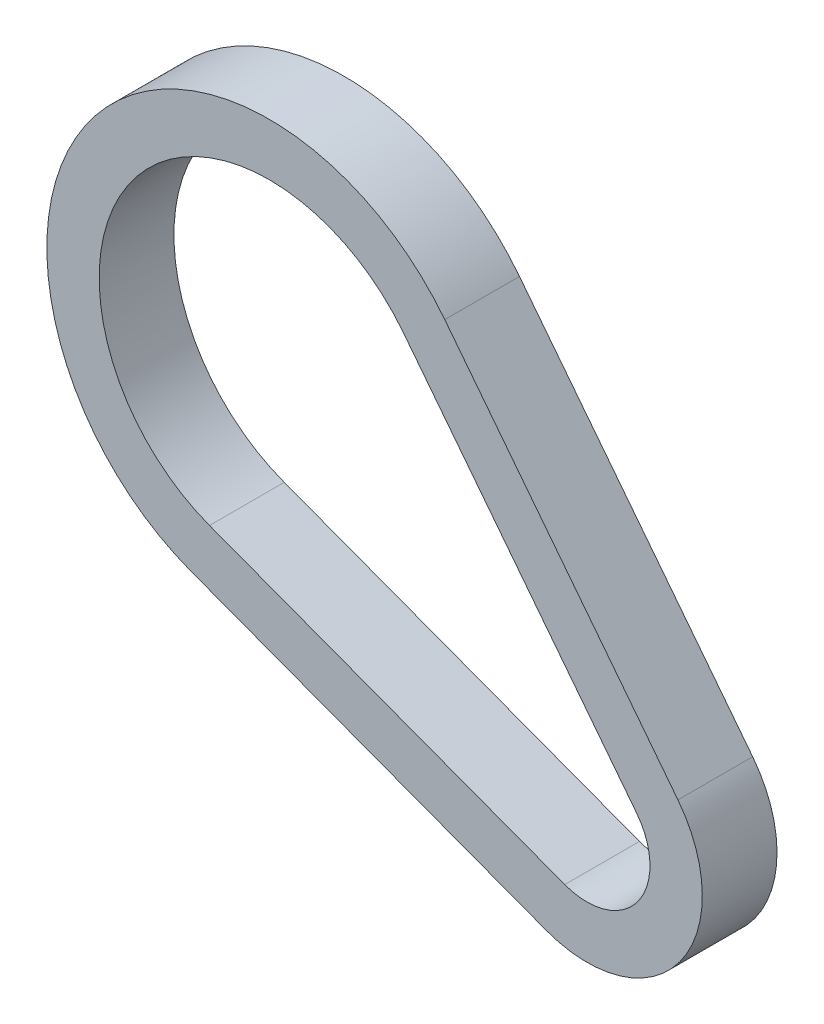
SolidWorks part; units mm, degrees
ref_plane "Front Plane" through (0, 0, 0) normal (0, 0, 1) x (1, 0, 0)
ref_plane "Top Plane" through (0, 0, 0) normal (0, 1, 0) x (1, 0, 0)
ref_plane "Right Plane" through (0, 0, 0) normal (1, 0, 0) x (0, 0, -1)
sketch "Sketch2" plane through (0, 0, 0) normal (0, 0, 1) x (1, 0, 0)
  line L0 (0, 0) -> (1, 0) construction
  line L1 (0, 0) -> (0, 1) construction
  line L2 (26.3108, 19.2245) -> (65.9345, -31.6442)
  line L3 (48.6478, -55.1526) -> (-11.7197, -32.4939)
  arc A0 (-11.7197, -32.4939) -> (26.3108, 19.2245) centre (0, -1.27) cw
  arc A1 (65.9345, -31.6442) -> (48.6478, -55.1526) centre (53.975, -40.9599) cw
extrude "Extrude-Thin1" add sketch "Sketch2" along normal mid plane 12.7 thin thin type mid plane wall 8.89
